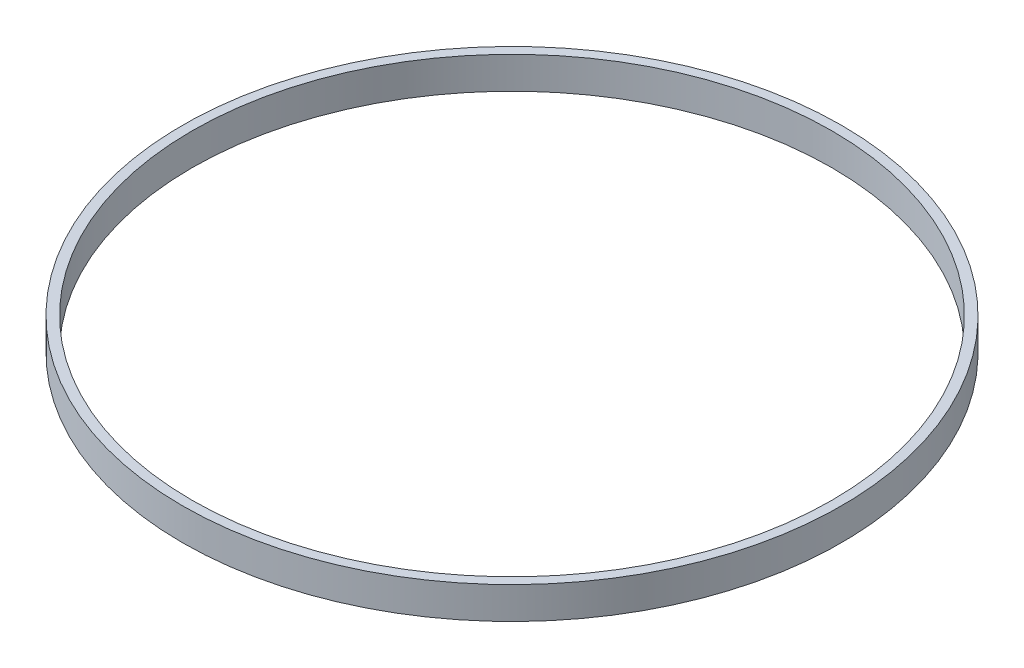
SolidWorks part; units mm, degrees
ref_plane "Front Plane" through (0, 0, 0) normal (0, 0, 1) x (1, 0, 0)
ref_plane "Top Plane" through (0, 0, 0) normal (0, 1, 0) x (1, 0, 0)
ref_plane "Right Plane" through (0, 0, 0) normal (1, 0, 0) x (0, 0, -1)
sketch "Sketch1" plane through (0, 0, 0) normal (0, 1, 0) x (1, 0, 0)
  circle A0 centre (0, 0) radius 100
  circle A1 centre (0, 0) radius 103
  dimension "D1" = 200
  dimension "D2" = 206
extrude "Boss-Extrude1" add sketch "Sketch1" along normal blind 10
sketch3d "URDF Reference"
  line L0 (0, 0, 0) -> (10, 0, 0) construction
  line L1 (0, 0, 0) -> (0, 0, -10) construction
  point P0 (0, 0, 0)
  point P1 (0, 0, 0)
